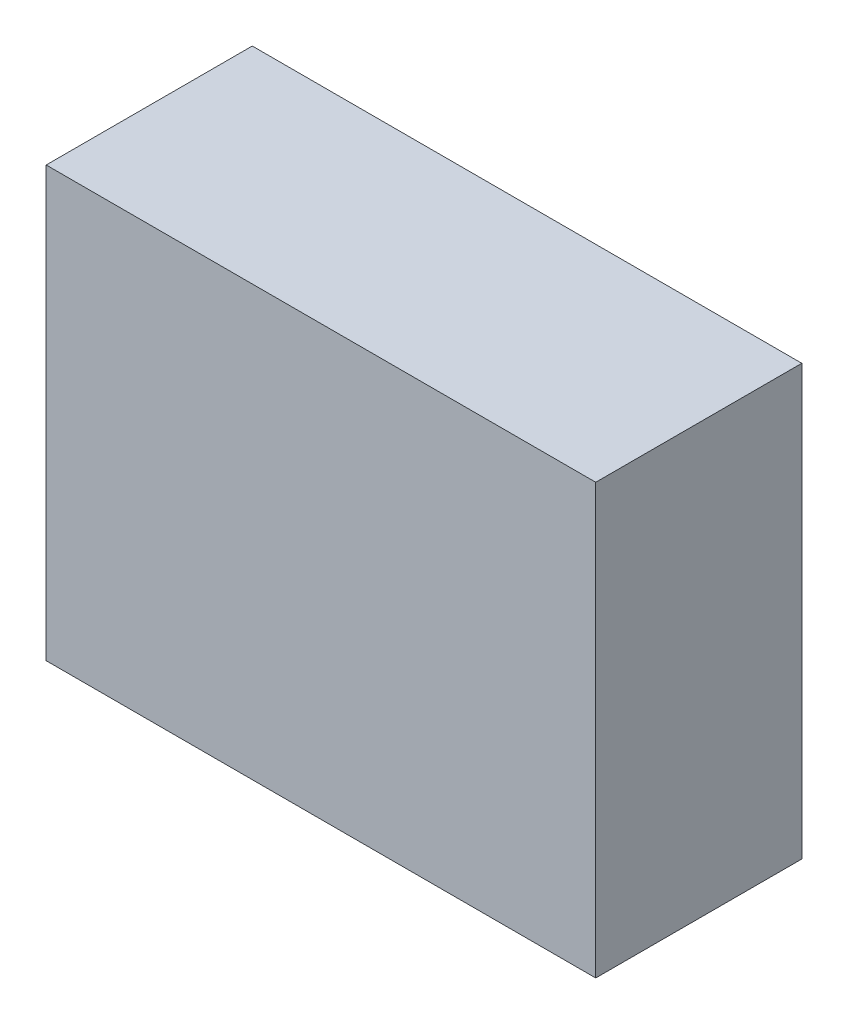
SolidWorks part; units mm, degrees
ref_plane "Front Plane" through (0, 0, 0) normal (0, 0, 1) x (1, 0, 0)
ref_plane "Top Plane" through (0, 0, 0) normal (0, 1, 0) x (1, 0, 0)
ref_plane "Right Plane" through (0, 0, 0) normal (1, 0, 0) x (0, 0, -1)
sketch "Sketch1" plane through (0, 0, 0) normal (0, 0, 1) x (1, 0, 0)
  line L1 (-24, -18.75) -> (24, -18.75)
  line L2 (-24, -18.75) -> (-24, 18.75)
  line L3 (-24, 18.75) -> (24, 18.75)
  line L4 (24, -18.75) -> (24, 18.75)
  line L5 (-24, -18.75) -> (24, 18.75) construction
  line L6 (-24, 18.75) -> (24, -18.75) construction
  point P0 (0, 0)
extrude "Envelope" add sketch "Sketch1" along normal blind 18
